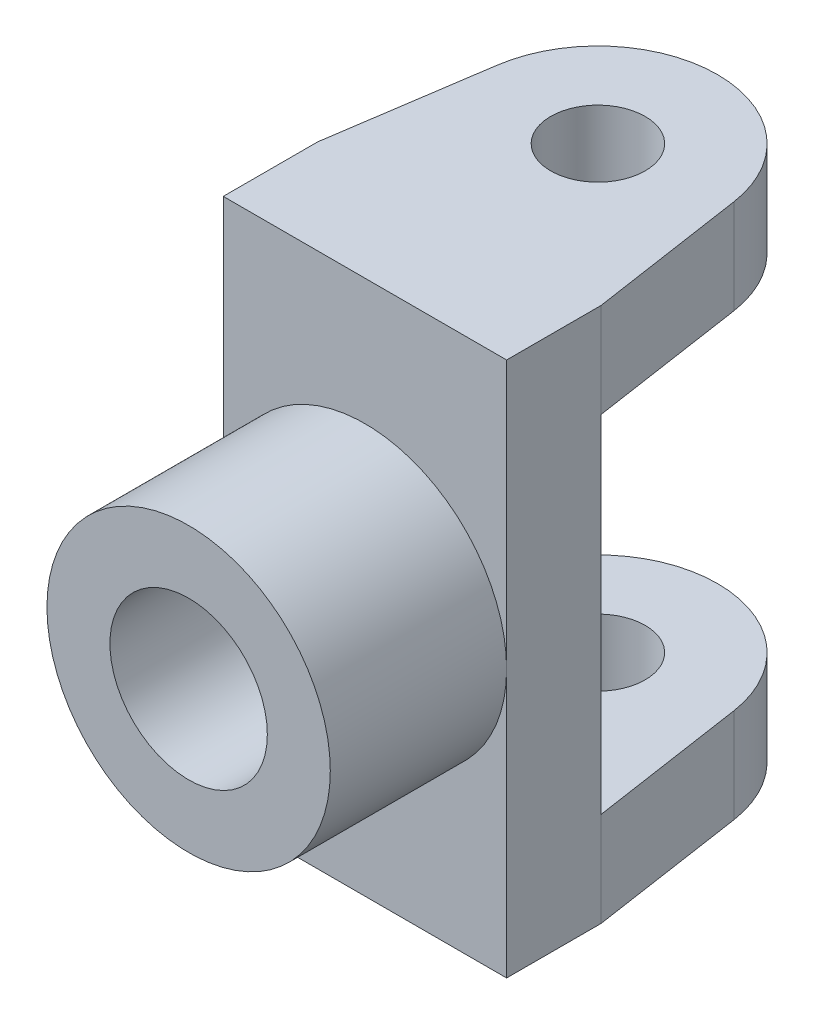
SolidWorks part; units mm, degrees
ref_plane "Front Plane" through (0, 0, 0) normal (0, 0, 1) x (1, 0, 0)
ref_plane "Top Plane" through (0, 0, 0) normal (0, 1, 0) x (1, 0, 0)
ref_plane "Right Plane" through (0, 0, 0) normal (1, 0, 0) x (0, 0, -1)
sketch "Sketch2" plane through (0, 0, 0) normal (0, 0, 1) x (1, 0, 0)
  line L1 (-45, 85) -> (45, 85)
  line L2 (-45, 85) -> (-45, -85)
  line L3 (-45, -85) -> (45, -85)
  line L4 (45, 85) -> (45, -85)
  line L5 (-45, 85) -> (45, -85) construction
  line L6 (-45, -85) -> (45, 85) construction
  point P0 (0, 0)
  dimension "D1" = 170
  dimension "D2" = 90
extrude "Boss-Extrude1" add sketch "Sketch2" against normal blind 30
sketch "Sketch3" plane through (0, 0, 0) normal (0, 0, 1) x (1, 0, 0)
  line L5 (-11.3201, 27.7097) -> (11.3201, 22.2903) construction
  line L6 (-11.3201, 22.2903) -> (11.3201, 27.7097) construction
  circle A0 centre (0, 0) radius 45
  circle A1 centre (0, 0) radius 25
  point P4 (0, 25)
  dimension "D1" = 90
  dimension "D2" = 50
  dimension "D3" = 25
extrude "Boss-Extrude2" add sketch "Sketch3" along normal blind 56
sketch "Sketch5" plane through (0, -85, 0) normal (0, -1, 0) x (1, 0, 0)
  line L0 (45, 0) -> (-45, 0) construction
  line L1 (45, -30) -> (37.5824, -79.6183)
  line L2 (-45, -30) -> (-37.5824, -79.6183)
  line L3 (-45, -30) -> (45, -30)
  arc A0 (-37.5824, -79.6183) -> (37.5824, -79.6183) centre (0, -74) ccw
  circle A1 centre (0, -74) radius 15
  dimension "D1" = 76
  dimension "D2" = 30
  dimension "D3" = 74
extrude "Boss-Extrude3" add sketch "Sketch5" against normal blind 30
mirror "Mirror1" about plane through (0, 0, 0) normal (0, 1, 0) of "Boss-Extrude3"
